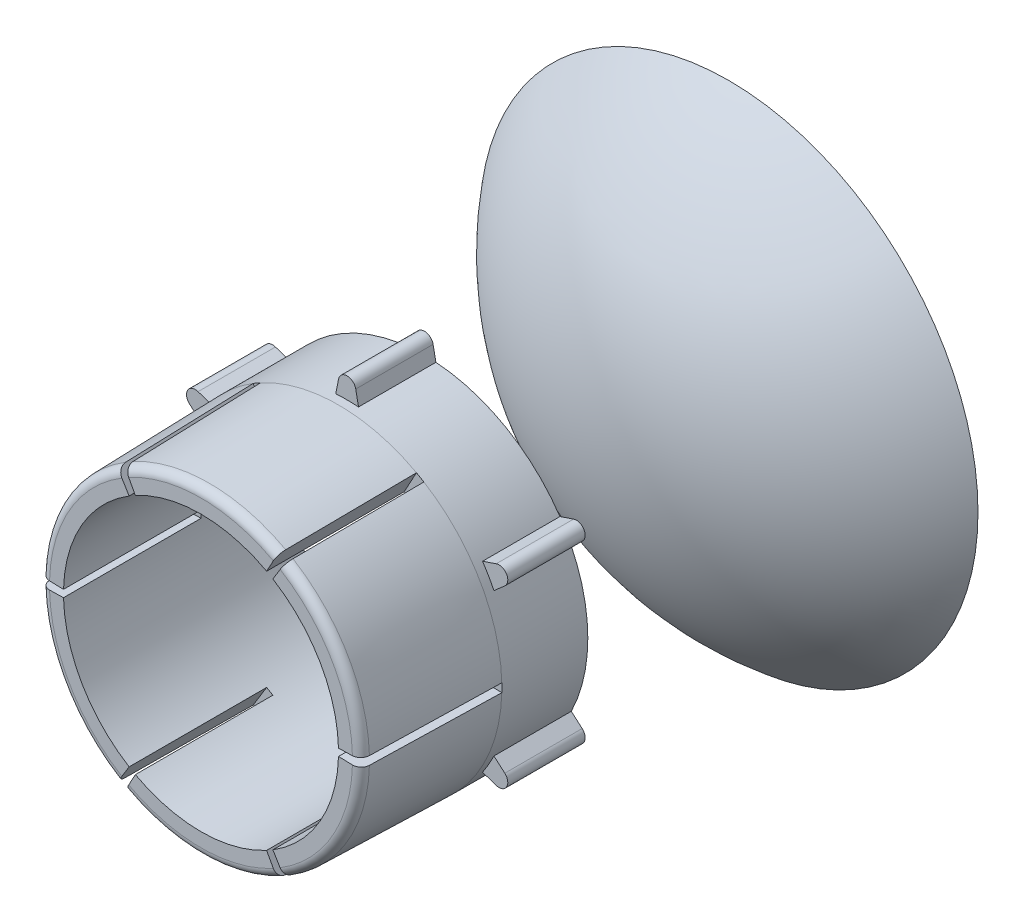
SolidWorks part; units mm, degrees
ref_plane "Front Plane" through (0, 0, 0) normal (0, 0, 1) x (1, 0, 0)
ref_plane "Top Plane" through (0, 0, 0) normal (0, 1, 0) x (1, 0, 0)
ref_plane "Right Plane" through (0, 0, 0) normal (1, 0, 0) x (0, 0, -1)
sketch "Sketch1" plane through (0, 0, 0) normal (0, 0, 1) x (1, 0, 0)
  circle A0 centre (0, 0) radius 9.5
  circle A1 centre (0, 0) radius 8
  dimension "D1" = 19
  dimension "D2" = 16
extrude "Boss-Extrude1" add sketch "Sketch1" along normal blind 13
sketch "Sketch2" plane through (0, 0, 0) normal (0, 1, 0) x (1, 0, 0)
  line L0 (9.5, -13) -> (9.5, -5)
  line L1 (9.5, -5) -> (9.3, -13)
  line L2 (9.3, -13) -> (9.5, -13)
  dimension "D1" = 8
  dimension "D2" = 0.2
sketch "Sketch3" plane through (0, 0, 13) normal (0, 0, 1) x (1, 0, 0)
  circle A0 centre (0, 0) radius 9.3
sweep "Cut-Sweep1" cut profiles "Sketch2" path "Sketch3"
sketch "Sketch4" plane through (0, 0, 13) normal (0, 0, 1) x (1, 0, 0)
  line L0 (-10.4973, -0.2749) -> (-7.9973, -0.2094)
  line L1 (-10.4973, 0.2749) -> (-7.9973, 0.2094)
  line L2 (-10.3763, 0) -> (10.6229, 0) construction
  line L3 (-10.4973, -0.2749) -> (0, 0) construction
  line L4 (0, 0) -> (-10.4973, 0.2749) construction
  line L5 (-5.1881, 8.9861) -> (5.3114, -9.1997) construction
  line L6 (-5.4867, 8.9535) -> (-4.18, 6.8211)
  line L7 (-5.0106, 9.2283) -> (-3.8173, 7.0305)
  line L8 (5.1881, 8.9861) -> (-5.3114, -9.1997) construction
  line L9 (5.0106, 9.2283) -> (3.8173, 7.0305)
  line L10 (5.4867, 8.9535) -> (4.18, 6.8211)
  line L11 (10.3763, 0) -> (-10.6229, 0) construction
  line L12 (10.4973, 0.2749) -> (7.9973, 0.2094)
  line L13 (10.4973, -0.2749) -> (7.9973, -0.2094)
  line L14 (5.1881, -8.9861) -> (-5.3114, 9.1997) construction
  line L15 (5.4867, -8.9535) -> (4.18, -6.8211)
  line L16 (5.0106, -9.2283) -> (3.8173, -7.0305)
  line L17 (-5.1881, -8.9861) -> (5.3114, 9.1997) construction
  line L18 (-5.0106, -9.2283) -> (-3.8173, -7.0305)
  line L19 (-5.4867, -8.9535) -> (-4.18, -6.8211)
  circle A1 centre (0, 0) radius 8 construction
  arc A2 (-10.4973, 0.2749) -> (-10.4973, -0.2749) centre (0, 0) ccw
  arc A3 (-7.9973, 0.2094) -> (-7.9973, -0.2094) centre (0, 0) ccw
  arc A4 (-3.8173, 7.0305) -> (-4.18, 6.8211) centre (0, 0) ccw
  arc A5 (-5.0106, 9.2283) -> (-5.4867, 8.9535) centre (0, 0) ccw
  arc A6 (4.18, 6.8211) -> (3.8173, 7.0305) centre (0, 0) ccw
  arc A7 (5.4867, 8.9535) -> (5.0106, 9.2283) centre (0, 0) ccw
  arc A8 (7.9973, -0.2094) -> (7.9973, 0.2094) centre (0, 0) ccw
  arc A9 (10.4973, -0.2749) -> (10.4973, 0.2749) centre (0, 0) ccw
  arc A10 (3.8173, -7.0305) -> (4.18, -6.8211) centre (0, 0) ccw
  arc A11 (5.0106, -9.2283) -> (5.4867, -8.9535) centre (0, 0) ccw
  arc A12 (-4.18, -6.8211) -> (-3.8173, -7.0305) centre (0, 0) ccw
  arc A13 (-5.4867, -8.9535) -> (-5.0106, -9.2283) centre (0, 0) ccw
  point P20 (-10.5009, 0)
  dimension "D1" = 3
  dimension "D3" = 2.5
  dimension "D2" = 6
extrude "Cut-Extrude1" cut sketch "Sketch4" against normal blind 8
fillet "Fillet1" radius 0.5 6 edges at (0, 9.3, 13) (-8.054, 4.65, 13) (-8.054, -4.65, 13) (0, -9.3, 13) (8.054, -4.65, 13) (8.054, 4.65, 13)
sketch "Sketch6" plane through (0, 0, 0) normal (0, 1, 0) x (1, 0, 0)
  line L0 (0, 17.6939) -> (14.5, 17.6939)
  line L3 (0, 17.6939) -> (0, 10.6939)
  line L4 (36.4723, 10.6939) -> (55.528, 10.6939) construction
  arc A0 (14.5, 17.6939) -> (0, 10.6939) centre (0, 29.2118) cw
  point P3 (61.5687, 0)
  point P4 (61.0199, -3.9515)
  point P10 (61.5687, 0)
  point P11 (46.6696, -0.8534)
  dimension "D1" = 7
  dimension "D2" = 14.5
revolve "Revolve1" add sketch "Sketch6" angle 360 about L3
sketch "Sketch8" plane through (0, 0, 0) normal (0, 0, -1) x (-1, 0, 0)
  line L0 (0, 0) -> (0.6627, 9.4769) construction
  line L1 (0, 0) -> (-0.6627, 9.4769) construction
  line L2 (0, -12.4646) -> (0, 14.0454) construction
  line L3 (-0.6627, 9.4769) -> (-0.5, 10.3)
  line L4 (-0.5, 10.3) -> (0.5, 10.3) construction
  line L5 (0.5, 10.3) -> (0.6627, 9.4769)
  line L6 (9.1701, 4.717) -> (8.5385, 4.1645)
  line L7 (7.8759, 5.3123) -> (8.6701, 5.583)
  line L8 (8.6701, -5.583) -> (7.8759, -5.3123)
  line L9 (8.5385, -4.1645) -> (9.1701, -4.717)
  line L10 (-0.5, -10.3) -> (-0.6627, -9.4769)
  line L11 (0.6627, -9.4769) -> (0.5, -10.3)
  line L12 (-9.1701, -4.717) -> (-8.5385, -4.1645)
  line L13 (-7.8759, -5.3123) -> (-8.6701, -5.583)
  line L14 (-8.6701, 5.583) -> (-7.8759, 5.3123)
  line L15 (-8.5385, 4.1645) -> (-9.1701, 4.717)
  arc A0 (-0.6627, 9.4769) -> (0.6627, 9.4769) centre (0, 0) cw
  circle A1 centre (0, 0) radius 9.5 construction
  arc A2 (-0.5, 10.3) -> (0.5, 10.3) centre (0, 10.2012) cw
  arc A3 (8.6701, 5.583) -> (9.1701, 4.717) centre (8.8345, 5.1006) cw
  arc A4 (7.8759, 5.3123) -> (8.5385, 4.1645) centre (0, 0) cw
  arc A5 (9.1701, -4.717) -> (8.6701, -5.583) centre (8.8345, -5.1006) cw
  arc A6 (8.5385, -4.1645) -> (7.8759, -5.3123) centre (0, 0) cw
  arc A7 (0.5, -10.3) -> (-0.5, -10.3) centre (0, -10.2012) cw
  arc A8 (0.6627, -9.4769) -> (-0.6627, -9.4769) centre (0, 0) cw
  arc A9 (-8.6701, -5.583) -> (-9.1701, -4.717) centre (-8.8345, -5.1006) cw
  arc A10 (-7.8759, -5.3123) -> (-8.5385, -4.1645) centre (0, 0) cw
  arc A11 (-9.1701, 4.717) -> (-8.6701, 5.583) centre (-8.8345, 5.1006) cw
  arc A12 (-8.5385, 4.1645) -> (-7.8759, 5.3123) centre (0, 0) cw
  point P3 (0, 9.5)
  point P4 (0, 10.3)
  dimension "D3" = 0.8
  dimension "D1" = 8
  dimension "D2" = 1
  dimension "D4" = 6
extrude "Boss-Extrude2" add sketch "Sketch8" against normal blind 4.5
sketch "Sketch9" plane through (0, 0, -17.6939) normal (0, 0, -1) x (-1, 0, 0)
  line L0 (0.746, 9.571) -> (0.5981, 10.3194)
  line L1 (-0.5981, 10.3194) -> (-0.746, 9.571)
  line L2 (-7.9157, 5.4316) -> (-8.6378, 5.6777)
  line L3 (-9.2359, 4.6417) -> (-8.6617, 4.1394)
  line L4 (-8.6617, -4.1394) -> (-9.2359, -4.6417)
  line L5 (-8.6378, -5.6777) -> (-7.9157, -5.4316)
  line L6 (-0.746, -9.571) -> (-0.5981, -10.3194)
  line L7 (0.5981, -10.3194) -> (0.746, -9.571)
  line L8 (7.9157, -5.4316) -> (8.6378, -5.6777)
  line L9 (9.2359, -4.6417) -> (8.6617, -4.1394)
  line L10 (8.6617, 4.1394) -> (9.2359, 4.6417)
  line L11 (8.6378, 5.6777) -> (7.9157, 5.4316)
  line L12 (0.6627, 9.4769) -> (0.5, 10.3)
  line L13 (-0.5, 10.3) -> (-0.6627, 9.4769)
  line L14 (-7.8759, 5.3123) -> (-8.6701, 5.583)
  line L15 (-9.1701, 4.717) -> (-8.5385, 4.1645)
  line L16 (-8.5385, -4.1645) -> (-9.1701, -4.717)
  line L17 (-8.6701, -5.583) -> (-7.8759, -5.3123)
  line L18 (-0.6627, -9.4769) -> (-0.5, -10.3)
  line L19 (0.5, -10.3) -> (0.6627, -9.4769)
  line L20 (7.8759, -5.3123) -> (8.6701, -5.583)
  line L21 (9.1701, -4.717) -> (8.5385, -4.1645)
  line L22 (8.5385, 4.1645) -> (9.1701, 4.717)
  line L23 (8.6701, 5.583) -> (7.8759, 5.3123)
  line L24 (0.6627, 9.4769) -> (0.5, 10.3) construction
  line L25 (-0.5, 10.3) -> (-0.6627, 9.4769) construction
  line L26 (-7.8759, 5.3123) -> (-8.6701, 5.583) construction
  line L27 (-9.1701, 4.717) -> (-8.5385, 4.1645) construction
  line L28 (-8.5385, -4.1645) -> (-9.1701, -4.717) construction
  line L29 (-8.6701, -5.583) -> (-7.8759, -5.3123) construction
  line L30 (-0.6627, -9.4769) -> (-0.5, -10.3) construction
  line L31 (0.5, -10.3) -> (0.6627, -9.4769) construction
  line L32 (7.8759, -5.3123) -> (8.6701, -5.583) construction
  line L33 (9.1701, -4.717) -> (8.5385, -4.1645) construction
  line L34 (8.5385, 4.1645) -> (9.1701, 4.717) construction
  line L35 (8.6701, 5.583) -> (7.8759, 5.3123) construction
  circle A0 centre (0, 0) radius 8 construction
  circle A1 centre (0, 0) radius 8 construction
  arc A2 (0.5981, 10.3194) -> (-0.5981, 10.3194) centre (0, 10.2012) ccw
  arc A3 (-0.746, 9.571) -> (-7.9157, 5.4316) centre (0, 0) ccw
  arc A4 (-8.6378, 5.6777) -> (-9.2359, 4.6417) centre (-8.8345, 5.1006) ccw
  arc A5 (-8.6617, 4.1394) -> (-8.6617, -4.1394) centre (0, 0) ccw
  arc A6 (-9.2359, -4.6417) -> (-8.6378, -5.6777) centre (-8.8345, -5.1006) ccw
  arc A7 (-7.9157, -5.4316) -> (-0.746, -9.571) centre (0, 0) ccw
  arc A8 (-0.5981, -10.3194) -> (0.5981, -10.3194) centre (0, -10.2012) ccw
  arc A9 (0.746, -9.571) -> (7.9157, -5.4316) centre (0, 0) ccw
  arc A10 (8.6378, -5.6777) -> (9.2359, -4.6417) centre (8.8345, -5.1006) ccw
  arc A11 (8.6617, -4.1394) -> (8.6617, 4.1394) centre (0, 0) ccw
  arc A12 (7.8759, 5.3123) -> (0.6627, 9.4769) centre (0, 0) ccw
  arc A13 (0.5, 10.3) -> (-0.5, 10.3) centre (0, 10.2012) ccw
  arc A14 (-0.6627, 9.4769) -> (-7.8759, 5.3123) centre (0, 0) ccw
  arc A15 (-8.6701, 5.583) -> (-9.1701, 4.717) centre (-8.8345, 5.1006) ccw
  arc A16 (-8.5385, 4.1645) -> (-8.5385, -4.1645) centre (0, 0) ccw
  arc A17 (-9.1701, -4.717) -> (-8.6701, -5.583) centre (-8.8345, -5.1006) ccw
  arc A18 (-7.8759, -5.3123) -> (-0.6627, -9.4769) centre (0, 0) ccw
  arc A19 (-0.5, -10.3) -> (0.5, -10.3) centre (0, -10.2012) ccw
  arc A20 (0.6627, -9.4769) -> (7.8759, -5.3123) centre (0, 0) ccw
  arc A21 (8.6701, -5.583) -> (9.1701, -4.717) centre (8.8345, -5.1006) ccw
  arc A22 (8.5385, -4.1645) -> (8.5385, 4.1645) centre (0, 0) ccw
  arc A23 (9.1701, 4.717) -> (8.6701, 5.583) centre (8.8345, 5.1006) ccw
  arc A24 (7.8759, 5.3123) -> (0.6627, 9.4769) centre (0, 0) ccw construction
  arc A25 (0.5, 10.3) -> (-0.5, 10.3) centre (0, 10.2012) ccw construction
  arc A26 (-0.6627, 9.4769) -> (-7.8759, 5.3123) centre (0, 0) ccw construction
  arc A27 (-8.6701, 5.583) -> (-9.1701, 4.717) centre (-8.8345, 5.1006) ccw construction
  arc A28 (-8.5385, 4.1645) -> (-8.5385, -4.1645) centre (0, 0) ccw construction
  arc A29 (-9.1701, -4.717) -> (-8.6701, -5.583) centre (-8.8345, -5.1006) ccw construction
  arc A30 (-7.8759, -5.3123) -> (-0.6627, -9.4769) centre (0, 0) ccw construction
  arc A31 (-0.5, -10.3) -> (0.5, -10.3) centre (0, -10.2012) ccw construction
  arc A32 (0.6627, -9.4769) -> (7.8759, -5.3123) centre (0, 0) ccw construction
  arc A33 (8.6701, -5.583) -> (9.1701, -4.717) centre (8.8345, -5.1006) ccw construction
  arc A34 (8.5385, -4.1645) -> (8.5385, 4.1645) centre (0, 0) ccw construction
  arc A35 (9.1701, 4.717) -> (8.6701, 5.583) centre (8.8345, 5.1006) ccw construction
  arc A36 (9.2359, 4.6417) -> (8.6378, 5.6777) centre (8.8345, 5.1006) ccw
  arc A37 (7.9157, 5.4316) -> (0.746, 9.571) centre (0, 0) ccw
  circle A38 centre (0, 0) radius 7.9
  dimension "D1" = 0
  dimension "D2" = 0.1
  dimension "D3" = 0.1
extrude "Cut-Extrude3" cut sketch "Sketch9" against normal blind 1
